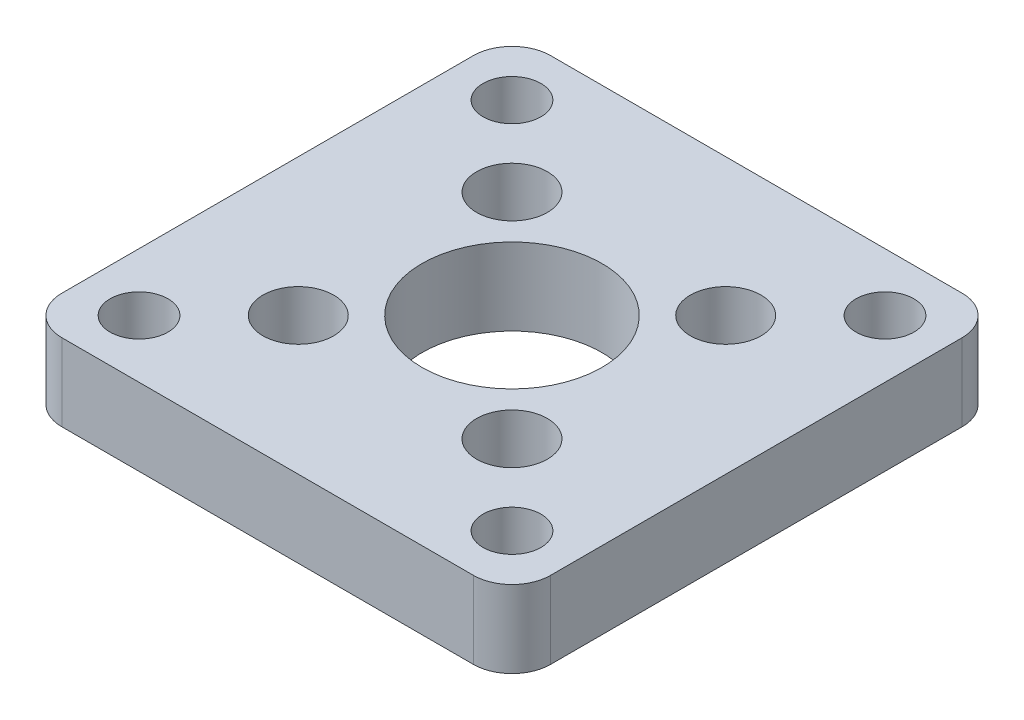
SolidWorks part; units mm, degrees
ref_plane "前视基准面" through (0, 0, 0) normal (0, 0, 1) x (1, 0, 0)
ref_plane "上视基准面" through (0, 0, 0) normal (0, 1, 0) x (1, 0, 0)
ref_plane "右视基准面" through (0, 0, 0) normal (1, 0, 0) x (0, 0, -1)
sketch "草图1" plane through (0, 0, 0) normal (0, 1, 0) x (1, 0, 0)
  line L0 (0, 0) -> (0, 50.003) construction
  line L1 (-19, 19) -> (19, 19)
  line L2 (-19, 19) -> (-19, -19)
  line L3 (-19, -19) -> (19, -19)
  line L4 (19, 19) -> (19, -19)
  line L5 (0, 0) -> (75.069, 0) construction
  dimension "D1" = 38
extrude "凸台-拉伸1" add sketch "草图1" along normal mid plane 6
sketch "草图2" plane through (0, 3, 0) normal (0, 1, 0) x (1, 0, 0)
  line L0 (0, 0) -> (0, 15.4894) construction
  line L1 (0, 0) -> (-22.1096, 0) construction
  circle A0 centre (-14.5, 14.5) radius 2.25
  circle A1 centre (-14.5, -14.5) radius 2.25
  circle A2 centre (14.5, -14.5) radius 2.25
  circle A3 centre (14.5, 14.5) radius 2.25
  dimension "D3" = 4.5
  dimension "D1" = 29
  dimension "D2" = 29
extrude "切除-拉伸1" cut sketch "草图2" against normal through all
sketch "草图3" plane through (0, 3, 0) normal (0, 1, 0) x (1, 0, 0)
  line L0 (0, 0) -> (0, 14.039) construction
  line L1 (0, 0) -> (-16.3434, 0) construction
  line L2 (-8.3085, 8.3085) -> (0, 0) construction
  circle A0 centre (-8.3085, 8.3085) radius 2.75
  circle A1 centre (-8.3085, -8.3085) radius 2.75
  circle A2 centre (8.3085, -8.3085) radius 2.75
  circle A3 centre (8.3085, 8.3085) radius 2.75
  circle A4 centre (0, 0) radius 11.75 construction
  circle A5 centre (0, 0) radius 7
  dimension "D1" = 23.5
  dimension "D2" = 5.5
  dimension "D4" = 14
  dimension "D3" = 45
extrude "切除-拉伸2" cut sketch "草图3" against normal through all
fillet "圆角1" radius 3 4 edges at (-19, 0, -19) (-19, 0, 19) (19, 0, -19) (19, 0, 19)
